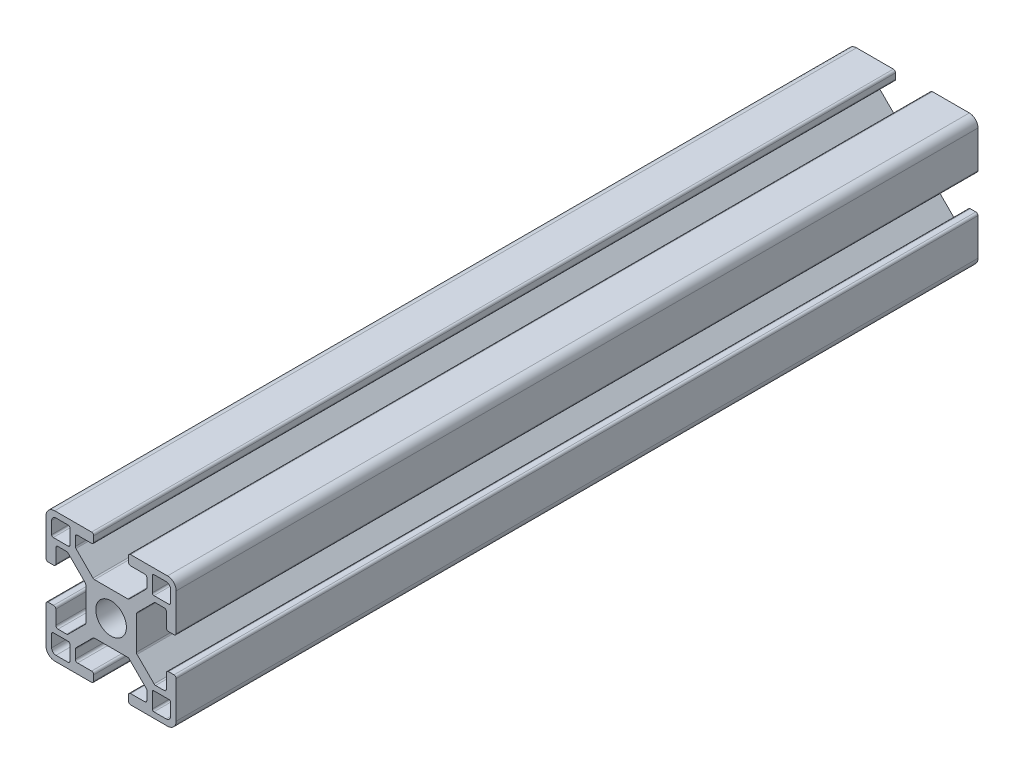
SolidWorks part; units mm, degrees
ref_plane "Front Plane" through (0, 0, 0) normal (0, 0, 1) x (1, 0, 0)
ref_plane "Top Plane" through (0, 0, 0) normal (0, 1, 0) x (1, 0, 0)
ref_plane "Right Plane" through (0, 0, 0) normal (1, 0, 0) x (0, 0, -1)
sketch "Sketch1" plane through (0, 0, 0) normal (0, 0, 1) x (1, 0, 0)
  line L0 (3.9799, -2.4733) -> (3.1981, -1.4942) construction
  line L1 (1.4942, -3.1981) -> (2.4733, -3.9799) construction
  line L2 (-2.4733, -3.9799) -> (-1.4942, -3.1981) construction
  line L3 (-3.1981, -1.4942) -> (-3.9799, -2.4733) construction
  line L4 (-3.9799, 2.4733) -> (-3.1981, 1.4942) construction
  line L5 (-1.4942, 3.1981) -> (-2.4733, 3.9799) construction
  line L6 (2.4733, 3.9799) -> (1.4942, 3.1981) construction
  line L7 (3.1981, 1.4942) -> (3.9799, 2.4733) construction
  line L8 (-12.6999, -13.6999) -> (-9.881, -13.6999)
  line L9 (-13.6999, -9.881) -> (-13.6999, -12.6999)
  line L10 (-9.88, -9.5) -> (-13.3189, -9.5)
  line L11 (-9.5, -13.3189) -> (-9.5, -9.88)
  line L12 (13.6999, -12.6999) -> (13.6999, -9.881)
  line L13 (9.881, -13.6999) -> (12.6999, -13.6999)
  line L14 (9.5, -9.88) -> (9.5, -13.3189)
  line L15 (13.3189, -9.5) -> (9.88, -9.5)
  line L16 (9.88, 9.5) -> (13.3189, 9.5)
  line L17 (9.5, 13.3189) -> (9.5, 9.88)
  line L18 (12.6999, 13.6999) -> (9.881, 13.6999)
  line L19 (13.6999, 9.881) -> (13.6999, 12.6999)
  line L20 (-13.6999, 12.6999) -> (-13.6999, 9.881)
  line L21 (-9.881, 13.6999) -> (-12.6999, 13.6999)
  line L22 (-9.5, 9.88) -> (-9.5, 13.3189)
  line L23 (-13.3189, 9.5) -> (-9.88, 9.5)
  line L24 (14.4999, -4) -> (13.2425, -4)
  line L25 (12.7425, -4.5) -> (12.7425, -7.7325)
  line L26 (12.2428, -8.25) -> (10.2602, -8.25)
  line L27 (9.9066, -8.1035) -> (5.9811, -4.178)
  line L28 (5.8347, -3.8245) -> (5.8347, -1.0125)
  line L29 (5.8347, -1.0125) -> (5.3247, -0.0625) construction
  line L30 (5.3247, -0.0625) -> (5.8347, 0.8875) construction
  line L31 (5.8347, 0.8875) -> (5.8347, 3.8245)
  line L32 (5.9811, 4.178) -> (9.9066, 8.1035)
  line L33 (10.2602, 8.25) -> (12.2428, 8.25)
  line L34 (12.7425, 7.7325) -> (12.7425, 4.5)
  line L35 (13.2425, 4) -> (14.4999, 4)
  line L36 (14.9999, 4.5) -> (14.9999, 12.9999)
  line L37 (12.9999, 14.9999) -> (4.5, 14.9999)
  line L38 (4, 14.4999) -> (4, 13.2425)
  line L39 (4.5, 12.7425) -> (7.7325, 12.7425)
  line L40 (8.25, 12.2428) -> (8.25, 10.2602)
  line L41 (8.1035, 9.9066) -> (4.178, 5.9811)
  line L42 (3.8245, 5.8347) -> (0.95, 5.8347)
  line L43 (0.95, 5.8347) -> (0, 5.3247) construction
  line L44 (0, 5.3247) -> (-0.95, 5.8347) construction
  line L45 (-0.95, 5.8347) -> (-3.8245, 5.8347)
  line L46 (-4.178, 5.9811) -> (-8.1035, 9.9066)
  line L47 (-8.25, 10.2602) -> (-8.25, 12.2428)
  line L48 (-7.7325, 12.7425) -> (-4.5, 12.7425)
  line L49 (-4, 13.2425) -> (-4, 14.4999)
  line L50 (-4.5, 14.9999) -> (-12.9999, 14.9999)
  line L51 (-14.9999, 12.9999) -> (-14.9999, 4.5)
  line L52 (-14.4999, 4) -> (-13.2425, 4)
  line L53 (-12.7425, 4.5) -> (-12.7425, 7.7325)
  line L54 (-12.2428, 8.25) -> (-10.2602, 8.25)
  line L55 (-9.9066, 8.1035) -> (-5.9811, 4.178)
  line L56 (-5.8347, 3.8245) -> (-5.8347, 0.8875)
  line L57 (-5.8347, 0.8875) -> (-5.3247, -0.0625) construction
  line L58 (-5.3247, -0.0625) -> (-5.8347, -1.0125) construction
  line L59 (-5.8347, -1.0125) -> (-5.8347, -3.8245)
  line L60 (-5.9811, -4.178) -> (-9.9066, -8.1035)
  line L61 (-10.2602, -8.25) -> (-12.2428, -8.25)
  line L62 (-12.7425, -7.7325) -> (-12.7425, -4.5)
  line L63 (-13.2425, -4) -> (-14.4999, -4)
  line L64 (-14.9999, -4.5) -> (-14.9999, -12.9999)
  line L65 (-12.9999, -14.9999) -> (-4.5, -14.9999)
  line L66 (-4, -14.4999) -> (-4, -13.2425)
  line L67 (-4.5, -12.7425) -> (-7.7325, -12.7425)
  line L68 (-8.25, -12.2428) -> (-8.25, -10.2602)
  line L69 (-8.1035, -9.9066) -> (-4.178, -5.9811)
  line L70 (-3.8245, -5.8347) -> (-0.95, -5.8347)
  line L71 (-0.95, -5.8347) -> (0, -5.3247) construction
  line L72 (0, -5.3247) -> (0.95, -5.8347) construction
  line L73 (0.95, -5.8347) -> (3.8245, -5.8347)
  line L74 (4.178, -5.9811) -> (8.1035, -9.9066)
  line L75 (8.25, -10.2602) -> (8.25, -12.2428)
  line L76 (7.7325, -12.7425) -> (4.5, -12.7425)
  line L77 (4, -13.2425) -> (4, -14.4999)
  line L78 (4.5, -14.9999) -> (12.9999, -14.9999)
  line L79 (14.9999, -12.9999) -> (14.9999, -4.5)
  line L80 (-5.8347, -1.0125) -> (-5.8347, 0.8875)
  line L81 (-0.95, 5.8347) -> (0.95, 5.8347)
  line L82 (5.8347, 0.8875) -> (5.8347, -1.0125)
  line L83 (-0.95, -5.8347) -> (0.95, -5.8347)
  arc A0 (2.4733, -3.9799) -> (3.9799, -2.4733) centre (3.1422, -3.1422) ccw construction
  arc A1 (-1.4942, -3.1981) -> (1.4942, -3.1981) centre (0, 0) ccw construction
  arc A2 (-3.9799, -2.4733) -> (-2.4733, -3.9799) centre (-3.1422, -3.1422) ccw construction
  arc A3 (-3.1981, 1.4942) -> (-3.1981, -1.4942) centre (0, 0) ccw construction
  arc A4 (-2.4733, 3.9799) -> (-3.9799, 2.4733) centre (-3.1422, 3.1422) ccw construction
  arc A5 (1.4942, 3.1981) -> (-1.4942, 3.1981) centre (0, 0) ccw construction
  arc A6 (3.9799, 2.4733) -> (2.4733, 3.9799) centre (3.1422, 3.1422) ccw construction
  arc A7 (3.1981, -1.4942) -> (3.1981, 1.4942) centre (0, 0) ccw construction
  arc A8 (-13.6999, -12.6999) -> (-12.6999, -13.6999) centre (-12.6999, -12.6999) ccw
  arc A9 (-13.3189, -9.5) -> (-13.6999, -9.881) centre (-13.3189, -9.881) ccw
  arc A10 (-9.5, -9.88) -> (-9.88, -9.5) centre (-9.88, -9.88) ccw
  arc A11 (-9.881, -13.6999) -> (-9.5, -13.3189) centre (-9.881, -13.3189) ccw
  arc A12 (12.6999, -13.6999) -> (13.6999, -12.6999) centre (12.6999, -12.6999) ccw
  arc A13 (9.5, -13.3189) -> (9.881, -13.6999) centre (9.881, -13.3189) ccw
  arc A14 (9.88, -9.5) -> (9.5, -9.88) centre (9.88, -9.88) ccw
  arc A15 (13.6999, -9.881) -> (13.3189, -9.5) centre (13.3189, -9.881) ccw
  arc A16 (9.5, 9.88) -> (9.88, 9.5) centre (9.88, 9.88) ccw
  arc A17 (9.881, 13.6999) -> (9.5, 13.3189) centre (9.881, 13.3189) ccw
  arc A18 (13.6999, 12.6999) -> (12.6999, 13.6999) centre (12.6999, 12.6999) ccw
  arc A19 (13.3189, 9.5) -> (13.6999, 9.881) centre (13.3189, 9.881) ccw
  arc A20 (14.9999, -4.5) -> (14.4999, -4) centre (14.4999, -4.5) ccw
  arc A21 (13.2425, -4) -> (12.7425, -4.5) centre (13.2425, -4.5) ccw
  arc A22 (12.2428, -8.25) -> (12.7425, -7.7325) centre (12.2428, -7.75) ccw
  arc A23 (9.9066, -8.1035) -> (10.2602, -8.25) centre (10.2602, -7.75) ccw
  arc A24 (5.8347, -3.8245) -> (5.9811, -4.178) centre (6.3347, -3.8245) ccw
  arc A25 (5.9811, 4.178) -> (5.8347, 3.8245) centre (6.3347, 3.8245) ccw
  arc A26 (10.2602, 8.25) -> (9.9066, 8.1035) centre (10.2602, 7.75) ccw
  arc A27 (12.7425, 7.7325) -> (12.2428, 8.25) centre (12.2428, 7.75) ccw
  arc A28 (12.7425, 4.5) -> (13.2425, 4) centre (13.2425, 4.5) ccw
  arc A29 (14.4999, 4) -> (14.9999, 4.5) centre (14.4999, 4.5) ccw
  arc A30 (14.9999, 12.9999) -> (12.9999, 14.9999) centre (12.9999, 12.9999) ccw
  arc A31 (4.5, 14.9999) -> (4, 14.4999) centre (4.5, 14.4999) ccw
  arc A32 (4, 13.2425) -> (4.5, 12.7425) centre (4.5, 13.2425) ccw
  arc A33 (8.25, 12.2428) -> (7.7325, 12.7425) centre (7.75, 12.2428) ccw
  arc A34 (8.1035, 9.9066) -> (8.25, 10.2602) centre (7.75, 10.2602) ccw
  arc A35 (3.8245, 5.8347) -> (4.178, 5.9811) centre (3.8245, 6.3347) ccw
  arc A36 (-4.178, 5.9811) -> (-3.8245, 5.8347) centre (-3.8245, 6.3347) ccw
  arc A37 (-8.25, 10.2602) -> (-8.1035, 9.9066) centre (-7.75, 10.2602) ccw
  arc A38 (-7.7325, 12.7425) -> (-8.25, 12.2428) centre (-7.75, 12.2428) ccw
  arc A39 (-4.5, 12.7425) -> (-4, 13.2425) centre (-4.5, 13.2425) ccw
  arc A40 (-4, 14.4999) -> (-4.5, 14.9999) centre (-4.5, 14.4999) ccw
  arc A41 (-12.9999, 14.9999) -> (-14.9999, 12.9999) centre (-12.9999, 12.9999) ccw
  arc A42 (-14.9999, 4.5) -> (-14.4999, 4) centre (-14.4999, 4.5) ccw
  arc A43 (-13.2425, 4) -> (-12.7425, 4.5) centre (-13.2425, 4.5) ccw
  arc A44 (-12.2428, 8.25) -> (-12.7425, 7.7325) centre (-12.2428, 7.75) ccw
  arc A45 (-9.9066, 8.1035) -> (-10.2602, 8.25) centre (-10.2602, 7.75) ccw
  arc A46 (-5.8347, 3.8245) -> (-5.9811, 4.178) centre (-6.3347, 3.8245) ccw
  arc A47 (-5.9811, -4.178) -> (-5.8347, -3.8245) centre (-6.3347, -3.8245) ccw
  arc A48 (-10.2602, -8.25) -> (-9.9066, -8.1035) centre (-10.2602, -7.75) ccw
  arc A49 (-12.7425, -7.7325) -> (-12.2428, -8.25) centre (-12.2428, -7.75) ccw
  arc A50 (-12.7425, -4.5) -> (-13.2425, -4) centre (-13.2425, -4.5) ccw
  arc A51 (-14.4999, -4) -> (-14.9999, -4.5) centre (-14.4999, -4.5) ccw
  arc A52 (-14.9999, -12.9999) -> (-12.9999, -14.9999) centre (-12.9999, -12.9999) ccw
  arc A53 (-4.5, -14.9999) -> (-4, -14.4999) centre (-4.5, -14.4999) ccw
  arc A54 (-4, -13.2425) -> (-4.5, -12.7425) centre (-4.5, -13.2425) ccw
  arc A55 (-8.25, -12.2428) -> (-7.7325, -12.7425) centre (-7.75, -12.2428) ccw
  arc A56 (-8.1035, -9.9066) -> (-8.25, -10.2602) centre (-7.75, -10.2602) ccw
  arc A57 (-3.8245, -5.8347) -> (-4.178, -5.9811) centre (-3.8245, -6.3347) ccw
  arc A58 (4.178, -5.9811) -> (3.8245, -5.8347) centre (3.8245, -6.3347) ccw
  arc A59 (8.25, -10.2602) -> (8.1035, -9.9066) centre (7.75, -10.2602) ccw
  arc A60 (7.7325, -12.7425) -> (8.25, -12.2428) centre (7.75, -12.2428) ccw
  arc A61 (4.5, -12.7425) -> (4, -13.2425) centre (4.5, -13.2425) ccw
  arc A62 (4, -14.4999) -> (4.5, -14.9999) centre (4.5, -14.4999) ccw
  arc A63 (12.9999, -14.9999) -> (14.9999, -12.9999) centre (12.9999, -12.9999) ccw
  arc A64 (-12.6999, 13.6999) -> (-13.6999, 12.6999) centre (-12.6999, 12.6999) ccw
  arc A65 (-9.5, 13.3189) -> (-9.881, 13.6999) centre (-9.881, 13.3189) ccw
  arc A66 (-9.88, 9.5) -> (-9.5, 9.88) centre (-9.88, 9.88) ccw
  arc A67 (-13.6999, 9.881) -> (-13.3189, 9.5) centre (-13.3189, 9.881) ccw
  circle A68 centre (0, 0) radius 3.53
extrude "Boss-Extrude1" add sketch "Sketch1" along normal mid plane 184.8
